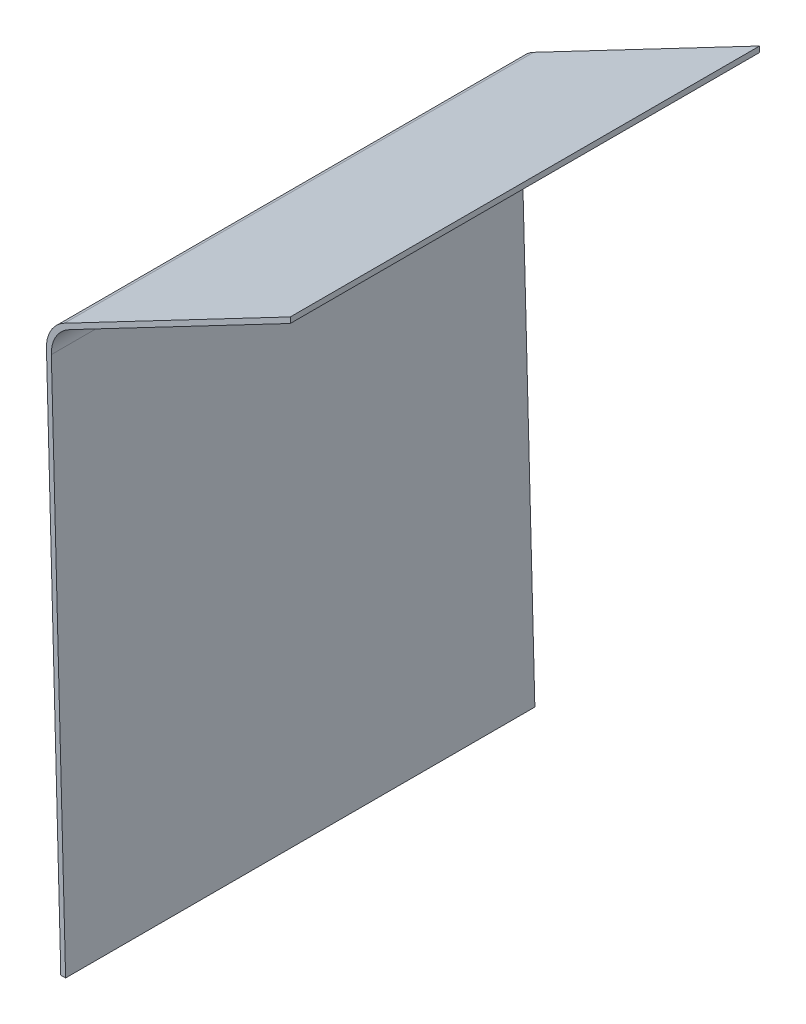
SolidWorks part; units mm, degrees
ref_plane "Front Plane" through (0, 0, 0) normal (0, 0, 1) x (1, 0, 0)
ref_plane "Top Plane" through (0, 0, 0) normal (0, 1, 0) x (1, 0, 0)
ref_plane "Right Plane" through (0, 0, 0) normal (1, 0, 0) x (0, 0, -1)
sketch "Sketch1" plane through (0, 0, 0) normal (0, 0, 1) x (1, 0, 0)
  line L0 (-6.985, -2.833) -> (-6.985, 2.833) construction
  line L2 (-6.985, 0) -> (-6.985, 1.5)
  line L6 (-6.985, 0) -> (-6.985, -1.5)
  line L7 (-6.985, -1.5) -> (-6.985, 1.5)
  line L8 (-144.05, -407.15) -> (-141.05, -407.15)
  line L9 (-141.7732, -69.1501) -> (-6.985, 1.5)
  line L10 (-144.05, -401.8235) -> (-144.05, -407.15)
  line L11 (-138.866, -71.0135) -> (-6.985, -1.8871)
  line L12 (-6.985, -1.5) -> (-6.985, -1.8871)
  line L13 (-163.2073, -83.7721) -> (-5.5923, -1.1571) construction
  line L14 (-164.6, -81.115) -> (-6.985, 1.5) construction
  line L15 (-144.05, -407.15) -> (-141.05, -407.15)
  line L16 (-144.05, -401.8235) -> (-152.481, -87.4003)
  line L17 (-141.05, -407.15) -> (-149.5739, -89.2637)
  arc A0 (-141.7732, -69.1501) -> (-152.481, -87.4003) centre (-132.4882, -86.8642) ccw
  arc A1 (-138.866, -71.0135) -> (-149.5739, -89.2637) centre (-129.581, -88.7276) ccw
  ellipse E0 centre (-98.941, -61.9789) end of major axis (-101.755, -61.9789) minor radius 1.221 construction
  ellipse E1 centre (-98.941, -61.9789) end of major axis (-101.755, -61.9789) minor radius 1.221
  dimension "D2" = 20
  dimension "D1" = 3
extrude "Boss-Extrude1" add sketch "Sketch1" against normal blind 280
